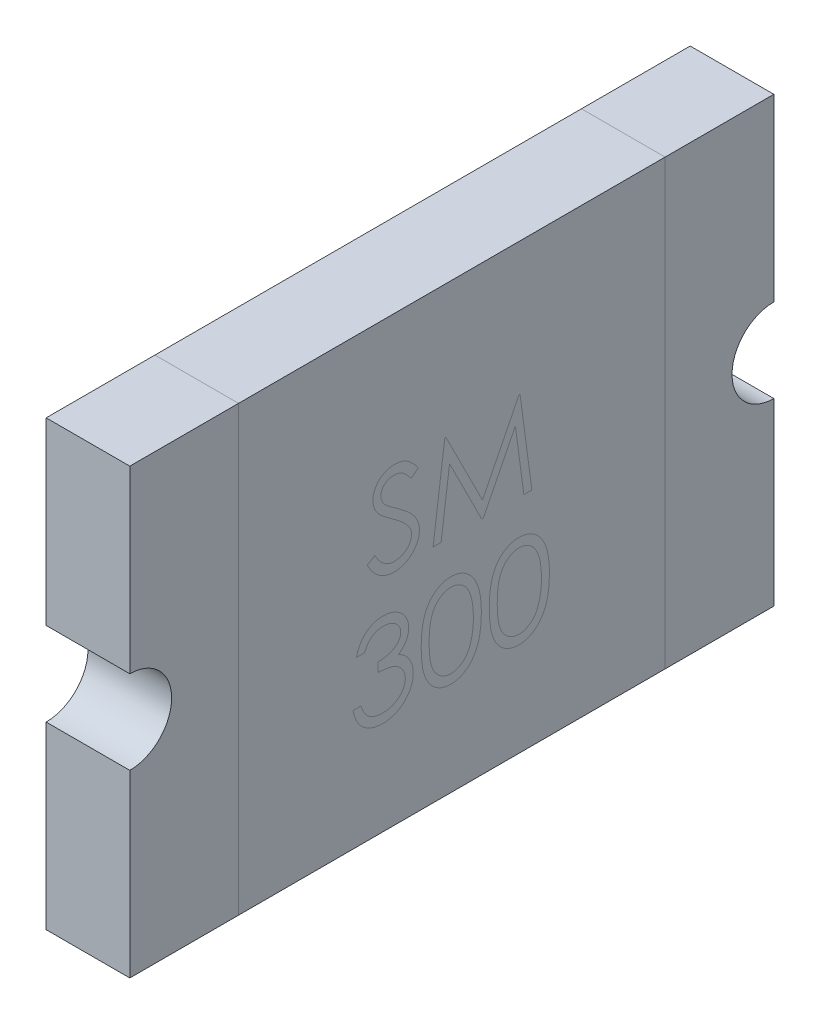
SolidWorks part; units mm, degrees
ref_plane "前视基准面" through (0, 0, 0) normal (0, 0, 1) x (1, 0, 0)
ref_plane "上视基准面" through (0, 0, 0) normal (0, 1, 0) x (1, 0, 0)
ref_plane "右视基准面" through (0, 0, 0) normal (1, 0, 0) x (0, 0, -1)
sketch "草图1" plane through (0, 0, 0) normal (1, 0, 0) x (0, 0, -1)
  line L0 (-6.7748, 0) -> (8.1135, 0) construction
  line L1 (0, -5.7364) -> (0, 5.6468) construction
  line L3 (-3.85, 2.65) -> (3.85, 2.65)
  line L4 (-3.85, 2.65) -> (-3.85, -2.65)
  line L5 (-3.85, -2.65) -> (3.85, -2.65)
  line L6 (3.85, 2.65) -> (3.85, -2.65)
  dimension "D1" = 5.3
  dimension "D2" = 7.7
  dimension "D3" = 3.85
  dimension "D4" = 2.65
extrude "凸台-拉伸1" add sketch "草图1" along normal blind 1
sketch "草图2" plane through (1, 0, 0) normal (1, 0, 0) x (0, 0, -1)
  line L0 (-4.7223, 0) -> (5.371, 0) construction
  line L1 (-3.85, -0.5) -> (-3.85, 0.5)
  line L2 (-3.85, 2.65) -> (-3.85, -2.65) construction
  line L3 (0, -3.9588) -> (0, 3.0102) construction
  line L4 (3.85, -0.5) -> (3.85, 0.5)
  arc A0 (-3.85, 0.5) -> (-3.85, -0.5) centre (-3.85, 0) cw
  arc A1 (3.85, 0.5) -> (3.85, -0.5) centre (3.85, 0) ccw
  dimension "D3" = 0.5
  dimension "D1" = 0.5
  dimension "D2" = 1
extrude "切除-拉伸1" cut sketch "草图2" against normal blind 1
sketch "草图3" plane through (1, 0, 0) normal (1, 0, 0) x (0, 0, -1)
  line L0 (-3.85, -2.65) -> (3.85, -2.65) construction
  line L1 (-3.85, 2.65) -> (-2.55, 2.65)
  line L2 (-3.85, 2.65) -> (-3.85, -2.65)
  line L3 (-3.85, -2.65) -> (-2.55, -2.65)
  line L4 (-2.55, 2.65) -> (-2.55, -2.65)
  line L5 (-2.55, 0) -> (2.55, 0) construction
  line L6 (3.85, 2.65) -> (2.55, 2.65)
  line L7 (3.85, 2.65) -> (3.85, -2.65)
  line L8 (3.85, -2.65) -> (2.55, -2.65)
  line L9 (2.55, 2.65) -> (2.55, -2.65)
  line L10 (-2.55, -1.5) -> (2.55, -1.5) construction
  line L11 (-2.55, 1.5) -> (2.55, 1.5) construction
  text T0 "SM" font "Century Gothic" height in points 3
  text T1 "300" font "Century Gothic" height in points 3
  dimension "D1" = 1.3
  dimension "D2" = 1.3
  dimension "D3" = 1.5
  dimension "D4" = 1.5
split line "分割线1"
sketch "草图4" plane through (0, 2.65, 0) normal (0, 1, 0) x (1, 0, 0)
  line L1 (1, 2.55) -> (0, 2.55)
  line L2 (1, 2.55) -> (1, 3.85)
  line L3 (1, 3.85) -> (0, 3.85)
  line L4 (0, 2.55) -> (0, 3.85)
  line L5 (1, -2.55) -> (0, -2.55)
  line L6 (1, -2.55) -> (1, -3.85)
  line L7 (1, -3.85) -> (0, -3.85)
  line L8 (0, -2.55) -> (0, -3.85)
split line "分割线2"
sketch "草图5" plane through (0, 0, 0) normal (-1, 0, 0) x (0, 0, 1)
  line L1 (-2.55, 2.65) -> (-3.85, 2.65)
  line L2 (-2.55, 2.65) -> (-2.55, -2.65)
  line L3 (-2.55, -2.65) -> (-3.85, -2.65)
  line L4 (-3.85, 2.65) -> (-3.85, -2.65)
  line L5 (2.55, 2.65) -> (3.85, 2.65)
  line L6 (2.55, 2.65) -> (2.55, -2.65)
  line L7 (2.55, -2.65) -> (3.85, -2.65)
  line L8 (3.85, 2.65) -> (3.85, -2.65)
split line "分割线3"
sketch "草图6" plane through (0, -2.65, 0) normal (0, -1, 0) x (1, 0, 0)
  line L1 (1, -2.55) -> (0, -2.55)
  line L2 (1, -2.55) -> (1, -3.85)
  line L3 (1, -3.85) -> (0, -3.85)
  line L4 (0, -2.55) -> (0, -3.85)
  line L5 (1, 2.55) -> (0, 2.55)
  line L6 (1, 2.55) -> (1, 3.85)
  line L7 (1, 3.85) -> (0, 3.85)
  line L8 (0, 2.55) -> (0, 3.85)
split line "分割线4"
